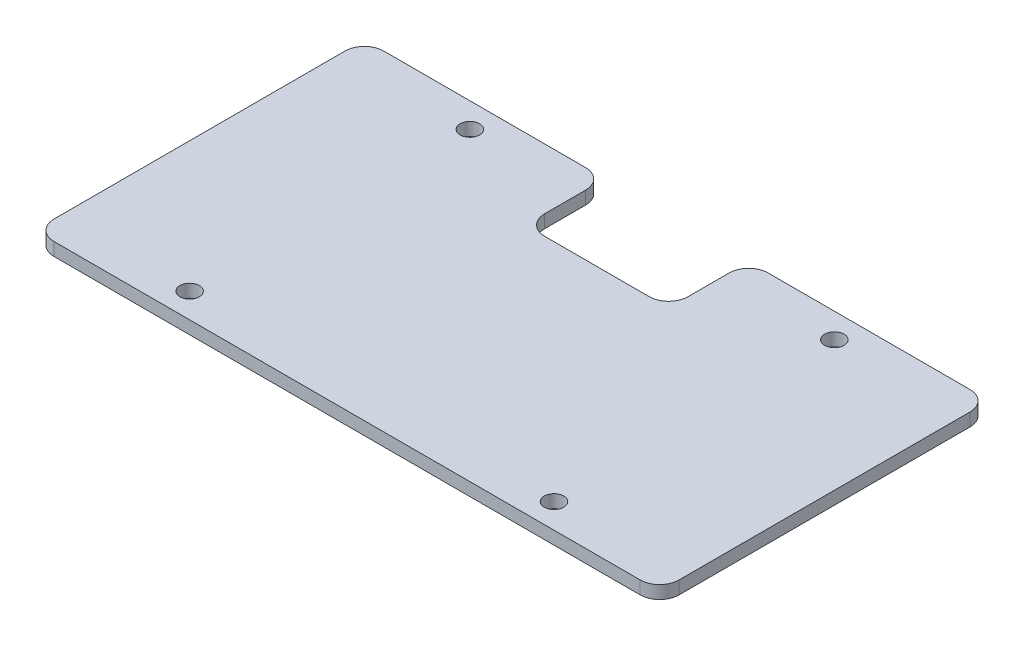
SolidWorks part; units mm, degrees
ref_plane "前视基准面" through (0, 0, 0) normal (0, 0, 1) x (1, 0, 0)
ref_plane "上视基准面" through (0, 0, 0) normal (0, 1, 0) x (1, 0, 0)
ref_plane "右视基准面" through (0, 0, 0) normal (1, 0, 0) x (0, 0, -1)
other "Configuration Table"
sketch "草图1" plane through (0, 0, 0) normal (0, 1, 0) x (1, 0, 0)
  line L0 (0, 0) -> (96.27, 0)
  line L1 (96.27, 0) -> (96.27, 50.8)
  line L2 (96.27, 50.8) -> (59.18, 50.8)
  line L3 (59.18, 50.8) -> (59.18, 38.48)
  line L4 (59.18, 38.48) -> (37.08, 38.48)
  line L5 (37.08, 38.48) -> (37.08, 50.8)
  line L6 (37.08, 50.8) -> (0, 50.8)
  line L7 (0, 50.8) -> (0, 0)
  line L8 (48.135, 0) -> (48.13, 38.48) construction
  line L9 (0, 25.4) -> (96.27, 25.4) construction
  circle A0 centre (20.0639, 46.9827) radius 1.5
  circle A1 centre (76.1939, 46.99) radius 1.5
  circle A2 centre (76.1939, 3.81) radius 1.5
  circle A3 centre (20.0639, 3.8173) radius 1.5
  point P10 (48.135, 0)
  point P12 (48.13, 38.48)
  dimension "D7" = 3
  dimension "D1" = 96.27
  dimension "D2" = 50.8
  dimension "D3" = 22.1
  dimension "D4" = 37.08
  dimension "D5" = 37.09
  dimension "D6" = 12.32
  dimension "D8" = 56.13
  dimension "D9" = 43.18
extrude "凸台-拉伸1" add sketch "草图1" along normal blind 2 contours A3 | A0 | A2 | L7 L0 L1 L2 L3 L4 L5 L6 | A1
fillet "圆角1" radius 3 8 edges at (0, 1, 0) (96.27, 1, 0) (96.27, 1, -50.8) (0, 1, -50.8) (59.18, 1, -38.48) (59.18, 1, -50.8) (37.08, 1, -38.48) (37.08, 1, -50.8)
